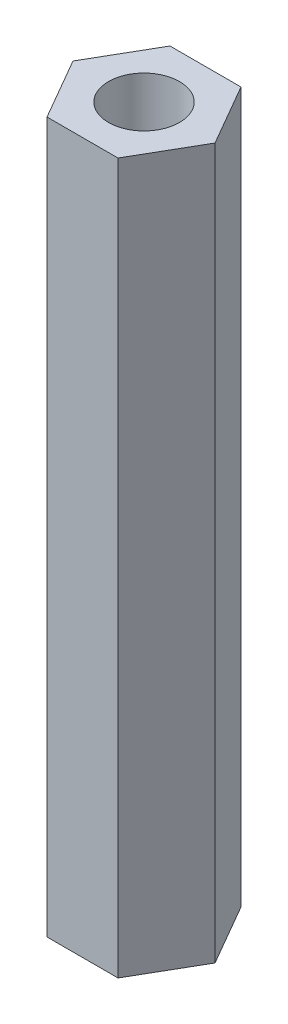
SolidWorks part; units mm, degrees
ref_plane "Front Plane" through (0, 0, 0) normal (0, 0, 1) x (1, 0, 0)
ref_plane "Top Plane" through (0, 0, 0) normal (0, 1, 0) x (1, 0, 0)
ref_plane "Right Plane" through (0, 0, 0) normal (1, 0, 0) x (0, 0, -1)
sketch "Sketch1" plane through (0, 0, 0) normal (0, 1, 0) x (1, 0, 0)
  line L1 (-1.5, -2.5981) -> (1.5, -2.5981)
  line L2 (1.5, -2.5981) -> (3, 0)
  line L3 (3, 0) -> (1.5, 2.5981)
  line L4 (1.5, 2.5981) -> (-1.5, 2.5981)
  line L5 (-1.5, 2.5981) -> (-3, 0)
  line L6 (-3, 0) -> (-1.5, -2.5981)
  circle A0 centre (0, 0) radius 2.5981 construction
  circle A1 centre (0, 0) radius 1.5
  dimension "D1" = 3
  dimension "D2" = 3
extrude "Boss-Extrude1" add sketch "Sketch1" along normal blind 30
